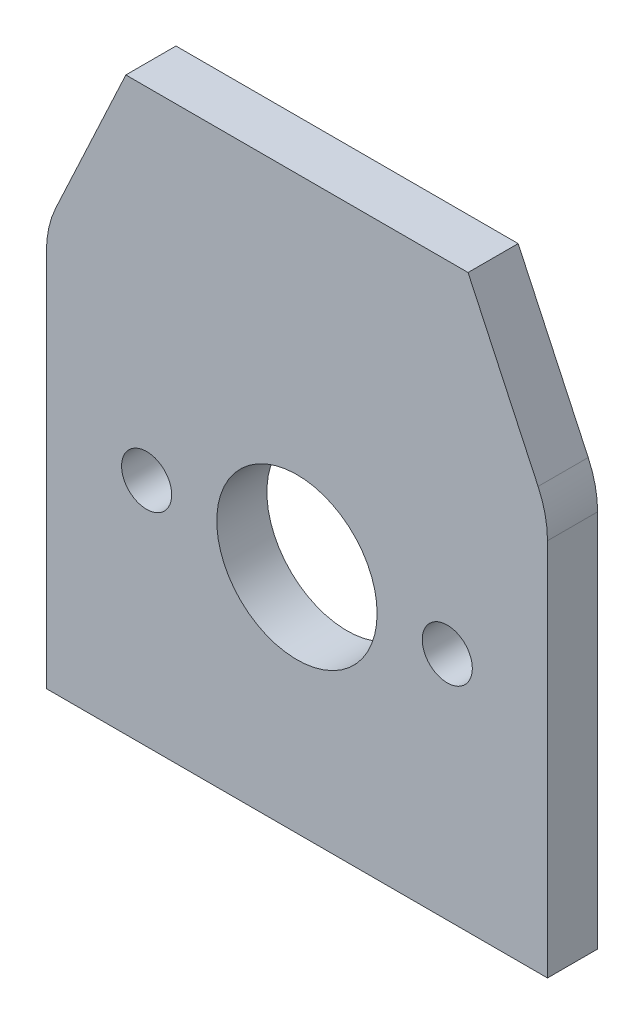
SolidWorks part; units mm, degrees
ref_plane "Front Plane" through (0, 0, 0) normal (0, 0, 1) x (1, 0, 0)
ref_plane "Top Plane" through (0, 0, 0) normal (0, 1, 0) x (1, 0, 0)
ref_plane "Right Plane" through (0, 0, 0) normal (1, 0, 0) x (0, 0, -1)
sketch "Sketch1" plane through (0, 0, 0) normal (0, 0, 1) x (1, 0, 0)
  line L0 (0, 0) -> (16183.6377, 0) construction
  line L1 (0, 0) -> (0, -16183.6377) construction
  line L2 (-25, 0) -> (-25, 37.7831)
  line L3 (-24.0631, 42.0092) -> (-17.0728, 57)
  line L4 (-17.0728, 57) -> (17.0728, 57)
  line L5 (25, 0) -> (25, 37.7831)
  line L6 (24.0631, 42.0092) -> (17.0728, 57)
  line L7 (-25, 0) -> (25, 0)
  arc A0 (-25, 37.7831) -> (-24.0631, 42.0092) centre (-15, 37.7831) cw
  arc A1 (25, 37.7831) -> (24.0631, 42.0092) centre (15, 37.7831) ccw
  circle A2 centre (0, 23) radius 8
  circle A3 centre (-15, 23) radius 2.5
  circle A4 centre (15, 23) radius 2.5
  point P11 (-25, 40)
  point P17 (0, 57)
  point P23 (0, 0)
  dimension "D5" = 10
  dimension "D6" = 16
  dimension "D8" = 5
  dimension "D9" = 10
  dimension "D10" = 10
  dimension "D1" = 50
  dimension "D2" = 155
  dimension "D3" = 57
  dimension "D4" = 17
  dimension "D7" = 23
extrude "Boss-Extrude1" add sketch "Sketch1" along normal mid plane 5
